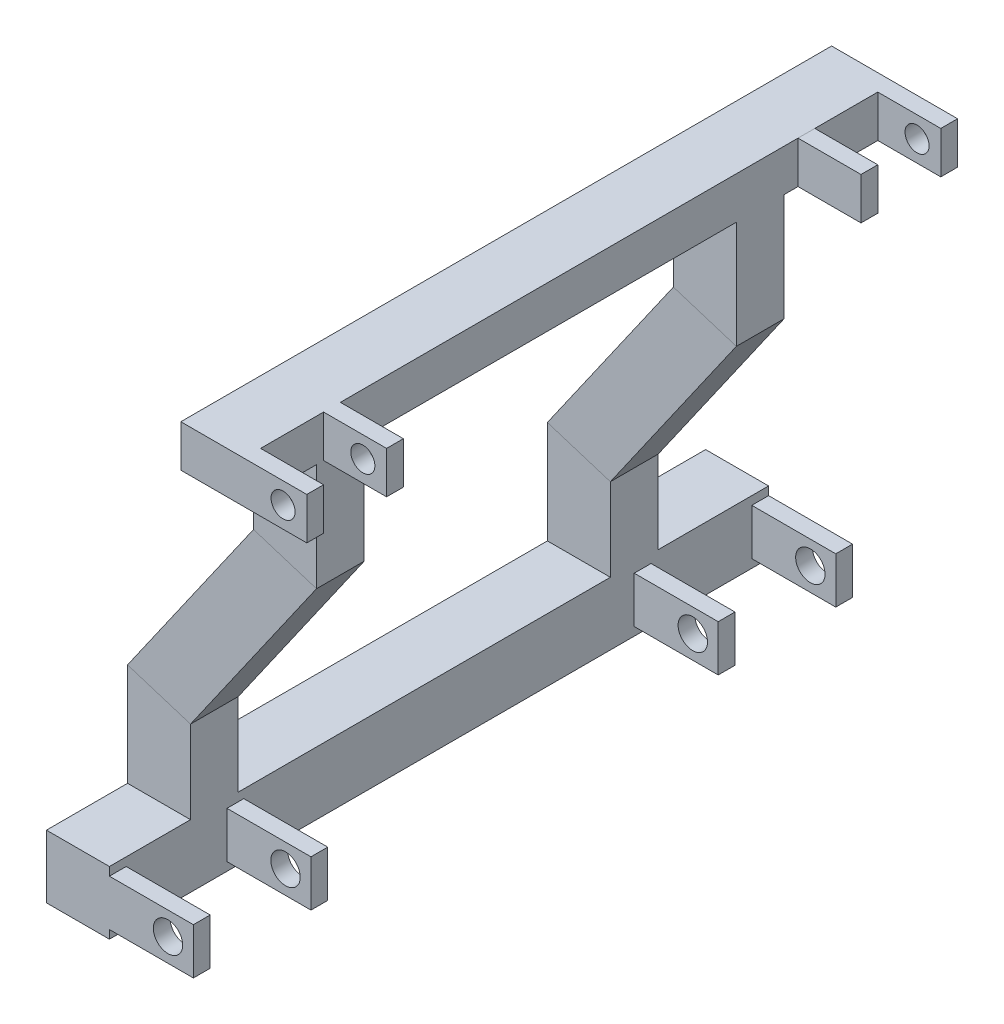
SolidWorks part; units mm, degrees
ref_plane "Front Plane" through (0, 0, 0) normal (0, 0, 1) x (1, 0, 0)
ref_plane "Top Plane" through (0, 0, 0) normal (0, 1, 0) x (1, 0, 0)
ref_plane "Right Plane" through (0, 0, 0) normal (1, 0, 0) x (0, 0, -1)
sketch "Sketch1" plane through (0, 0, 0) normal (0, 0, 1) x (1, 0, 0)
  line L0 (0, 0) -> (0, 100)
  line L1 (7.5, -7.5) -> (-7.5, -7.5)
  line L2 (7.5, -7.5) -> (7.5, 7.5)
  line L3 (7.5, 7.5) -> (-7.5, 7.5)
  line L4 (-7.5, -7.5) -> (-7.5, 7.5)
  line L5 (7.5, -7.5) -> (-7.5, 7.5) construction
  line L6 (7.5, 7.5) -> (-7.5, -7.5) construction
  line L12 (7.5, 92.5) -> (-7.5, 107.5) construction
  line L13 (7.5, 107.5) -> (-7.5, 92.5) construction
  point P0 (0, 0)
  dimension "D1" = 100
  dimension "D4" = 15
  dimension "D5" = 15
extrude "Boss-Extrude1" add sketch "Sketch1" along normal blind 100
sketch "Sketch5" plane through (0, 0, 0) normal (0, 0, 1) x (1, 0, 0)
  line L0 (0, -7.5) -> (0, 29.573)
  line L1 (7.5, -7.5) -> (-7.5, -7.5) construction
  line L2 (0, 29.573) -> (30.0108, 72.5031)
  line L3 (30.0108, 72.5031) -> (30.0108, 105.7487)
sketch "Sketch6" plane through (0, -7.5, 0) normal (0, -1, 0) x (1, 0, 0)
  line L1 (7.5, -5.6839) -> (-7.5, -5.6839)
  line L2 (7.5, -5.6839) -> (7.5, 5.6839)
  line L3 (7.5, 5.6839) -> (-7.5, 5.6839)
  line L4 (-7.5, -5.6839) -> (-7.5, 5.6839)
  line L5 (7.5, -5.6839) -> (-7.5, 5.6839) construction
  line L6 (7.5, 5.6839) -> (-7.5, -5.6839) construction
  point P0 (0, 0)
sweep "Sweep2" add profiles "Sketch6" path "Sketch5"
sketch "Sketch8" plane through (7.5, 0, 0) normal (1, 0, 0) x (0, 0, -1)
  line L0 (-50, 0) -> (-50, 20.7273) construction
ref_plane "Plane1" through (0, 0, 50) normal (0, 0, -1) x (0, 1, 0)
mirror "Mirror1" about plane through (0, 0, 50) normal (0, 0, -1) of bodies 105
sketch "Sketch9" plane through (0, 0, 5.6839) normal (0, 0, 1) x (1, 0, 0)
  line L1 (37.5108, 95.7487) -> (22.5108, 95.7487)
  line L2 (37.5108, 95.7487) -> (37.5108, 105.7487)
  line L3 (37.5108, 105.7487) -> (22.5108, 105.7487)
  line L4 (22.5108, 95.7487) -> (22.5108, 105.7487)
  line L5 (37.5108, 95.7487) -> (22.5108, 105.7487) construction
  line L6 (37.5108, 105.7487) -> (22.5108, 95.7487) construction
  point P0 (30.0108, 100.7487)
  dimension "D1" = 15
  dimension "D2" = 10
extrude "Boss-Extrude3" add sketch "Sketch9" along normal up to surface (88.6322 mm away) up to face at (30.0108, 89.1259, 94.3161)
sketch "Sketch10" plane through (7.5, 0, 0) normal (1, 0, 0) x (0, 0, -1)
  line L0 (-110.1184, 0) -> (9.677, 0) construction
  line L1 (-50, 9.8023) -> (-50, -11.4518) construction
  line L2 (-50, 0) -> (-50, 20.7273) construction
  line L3 (-50, -15.525) -> (-50, 15.525) construction
  line L5 (-121, -5.5) -> (-125, -5.5)
  line L6 (-121, -5.5) -> (-121, 5.5)
  line L7 (-121, 5.5) -> (-125, 5.5)
  line L8 (-125, -5.5) -> (-125, 5.5)
  line L9 (-121, -5.5) -> (-125, 5.5) construction
  line L10 (-121, 5.5) -> (-125, -5.5) construction
  line L11 (-93, -5.5) -> (-97, -5.5)
  line L12 (-93, -5.5) -> (-93, 5.5)
  line L13 (-93, 5.5) -> (-97, 5.5)
  line L14 (-97, -5.5) -> (-97, 5.5)
  line L15 (-93, -5.5) -> (-97, 5.5) construction
  line L16 (-93, 5.5) -> (-97, -5.5) construction
  line L17 (4, -5.5) -> (0, -5.5)
  line L18 (4, -5.5) -> (4, 5.5)
  line L19 (4, 5.5) -> (0, 5.5)
  line L20 (0, -5.5) -> (0, 5.5)
  line L21 (4, -5.5) -> (0, 5.5) construction
  line L22 (4, 5.5) -> (0, -5.5) construction
  line L23 (32, -5.5) -> (28, -5.5)
  line L24 (32, -5.5) -> (32, 5.5)
  line L25 (32, 5.5) -> (28, 5.5)
  line L26 (28, -5.5) -> (28, 5.5)
  line L27 (32, -5.5) -> (28, 5.5) construction
  line L28 (32, 5.5) -> (28, -5.5) construction
  point P9 (-123, 0)
  point P14 (-95, 0)
  point P19 (2, 0)
  point P24 (30, 0)
  dimension "D1" = 24
  dimension "D2" = 24
  dimension "D3" = 4
  dimension "D4" = 4
  dimension "D5" = 4
  dimension "D6" = 4
  dimension "D7" = 101
  dimension "D8" = 50
  dimension "D9" = 11
  dimension "D10" = 11
  dimension "D11" = 11
  dimension "D12" = 11
extrude "Boss-Extrude4" add sketch "Sketch10" along normal blind 20
sketch "Sketch13" plane through (0, 0, -5.6839) normal (0, 0, -1) x (-1, 0, 0)
  line L1 (7.5, 7.5) -> (-7.5, 7.5)
  line L2 (7.5, 7.5) -> (7.5, -7.5)
  line L3 (7.5, -7.5) -> (-7.5, -7.5)
  line L4 (-7.5, 7.5) -> (-7.5, -7.5)
  line L5 (7.5, 7.5) -> (-7.5, -7.5) construction
  line L6 (7.5, -7.5) -> (-7.5, 7.5) construction
  point P0 (0, 0)
extrude "Boss-Extrude5" add sketch "Sketch13" along normal up to surface (26.3161 mm away) up to face at (17.5, 0, -32)
sketch "Sketch14" plane through (0, 0, 105.6839) normal (0, 0, 1) x (1, 0, 0)
  line L1 (7.5, 7.5) -> (-7.5, 7.5)
  line L2 (7.5, 7.5) -> (7.5, -7.5)
  line L3 (7.5, -7.5) -> (-7.5, -7.5)
  line L4 (-7.5, 7.5) -> (-7.5, -7.5)
  line L5 (7.5, 7.5) -> (-7.5, -7.5) construction
  line L6 (7.5, -7.5) -> (-7.5, 7.5) construction
  point P0 (0, 0)
extrude "Boss-Extrude6" add sketch "Sketch14" along normal up to surface (19.3161 mm away) up to face at (17.5, 0, 125)
sketch "Sketch11" plane through (0, 0, 97) normal (0, 0, 1) x (1, 0, 0)
  circle A0 centre (21.4482, 0) radius 3.4986
extrude "Cut-Extrude1" cut sketch "Sketch11" against normal through all both and the other way through all
sketch "Sketch15" plane through (37.5108, 0, 0) normal (1, 0, 0) x (0, 0, -1)
  line L0 (-50, 105.7487) -> (-50, 95.7487) construction
  line L1 (5.6839, 105.7487) -> (-105.6839, 105.7487) construction
  line L2 (-94.3161, 95.7487) -> (-5.6839, 95.7487) construction
  line L3 (11.3241, 100.7487) -> (-111.3241, 100.7487) construction
  line L5 (-119, 95.7487) -> (-123, 95.7487)
  line L6 (-119, 95.7487) -> (-119, 105.7487)
  line L7 (-119, 105.7487) -> (-123, 105.7487)
  line L8 (-123, 95.7487) -> (-123, 105.7487)
  line L9 (-119, 95.7487) -> (-123, 105.7487) construction
  line L10 (-119, 105.7487) -> (-123, 95.7487) construction
  line L11 (-100, 95.7487) -> (-104, 95.7487)
  line L12 (-100, 95.7487) -> (-100, 105.7487)
  line L13 (-100, 105.7487) -> (-104, 105.7487)
  line L14 (-104, 95.7487) -> (-104, 105.7487)
  line L15 (-100, 95.7487) -> (-104, 105.7487) construction
  line L16 (-100, 105.7487) -> (-104, 95.7487) construction
  line L17 (13, 95.7487) -> (9, 95.7487)
  line L18 (13, 95.7487) -> (13, 105.7487)
  line L19 (13, 105.7487) -> (9, 105.7487)
  line L20 (9, 95.7487) -> (9, 105.7487)
  line L21 (13, 95.7487) -> (9, 105.7487) construction
  line L22 (13, 105.7487) -> (9, 95.7487) construction
  line L23 (32, 95.7487) -> (28, 95.7487)
  line L24 (32, 95.7487) -> (32, 105.7487)
  line L25 (32, 105.7487) -> (28, 105.7487)
  line L26 (28, 95.7487) -> (28, 105.7487)
  line L27 (32, 95.7487) -> (28, 105.7487) construction
  line L28 (32, 105.7487) -> (28, 95.7487) construction
  point P6 (-121, 100.7487)
  point P9 (-50, 100.7487)
  point P14 (-102, 100.7487)
  point P19 (11, 100.7487)
  point P24 (30, 100.7487)
  dimension "D1" = 117
  dimension "D2" = 54
  dimension "D3" = 4
  dimension "D4" = 4
  dimension "D5" = 4
  dimension "D6" = 4
  dimension "D7" = 10
  dimension "D8" = 10
  dimension "D9" = 10
  dimension "D10" = 10
  dimension "D11" = 15
  dimension "D12" = 15
extrude "Boss-Extrude7" add sketch "Sketch15" along normal blind 15
sketch "Sketch17" plane through (0, 0, 105.6839) normal (0, 0, 1) x (1, 0, 0)
  line L1 (22.5108, 105.7487) -> (37.5108, 105.7487)
  line L2 (22.5108, 105.7487) -> (22.5108, 95.7487)
  line L3 (22.5108, 95.7487) -> (37.5108, 95.7487)
  line L4 (37.5108, 105.7487) -> (37.5108, 95.7487)
extrude "Boss-Extrude8" add sketch "Sketch17" along normal up to surface (17.3161 mm away) up to face at (45.0108, 100.7487, 123)
sketch "Sketch18" plane through (0, 0, -5.6839) normal (0, 0, -1) x (-1, 0, 0)
  line L0 (-22.5108, 74.8647) -> (-22.5108, 105.7487) construction
  line L1 (-37.5108, 105.7487) -> (-22.5108, 105.7487)
  line L2 (-37.5108, 105.7487) -> (-37.5108, 95.7487)
  line L3 (-37.5108, 95.7487) -> (-22.5108, 95.7487)
  line L4 (-22.5108, 105.7487) -> (-22.5108, 95.7487)
extrude "Boss-Extrude9" add sketch "Sketch18" along normal up to surface (26.3161 mm away)
sketch "Sketch19" plane through (0, 0, -32) normal (0, 0, -1) x (-1, 0, 0)
  circle A0 centre (-46.8623, 100.7487) radius 2.8658
extrude "Cut-Extrude2" cut sketch "Sketch19" against normal through all and the other way through all
